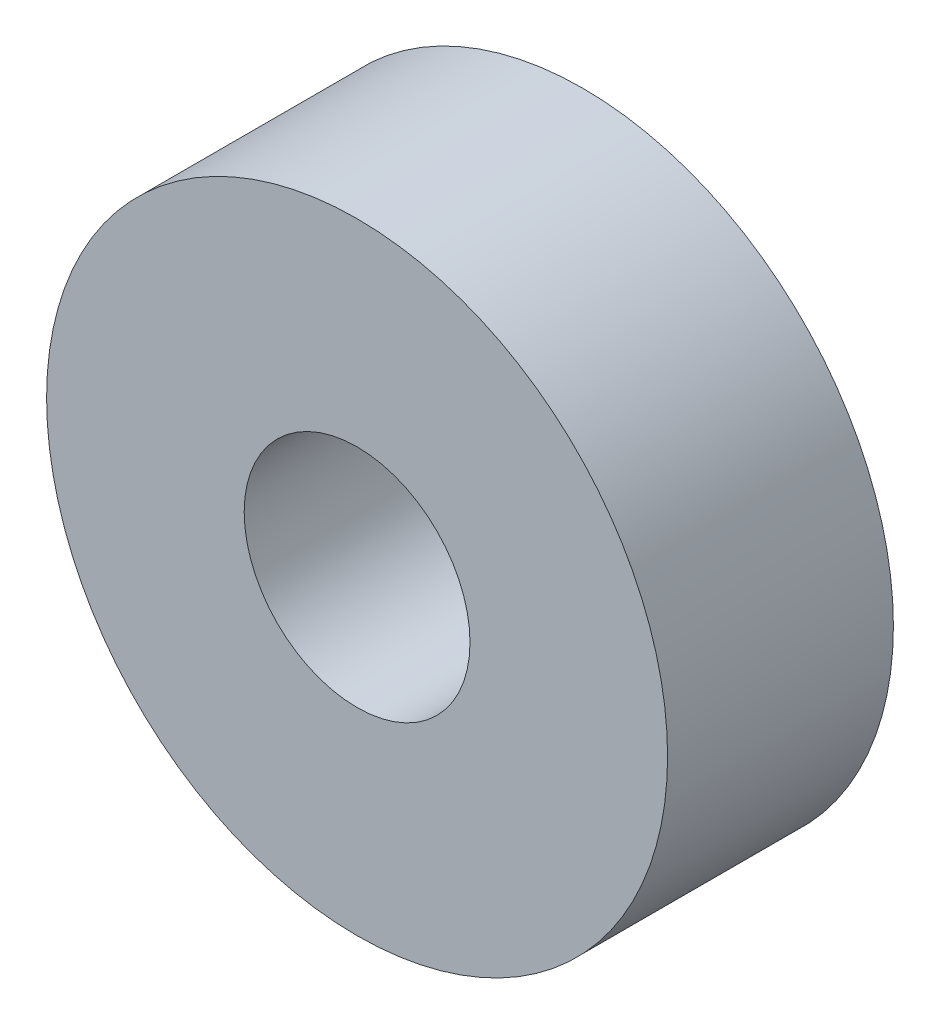
SolidWorks part; units mm, degrees
ref_plane "Спереди" through (0, 0, 0) normal (0, 0, 1) x (1, 0, 0)
ref_plane "Сверху" through (0, 0, 0) normal (0, 1, 0) x (1, 0, 0)
ref_plane "Справа" through (0, 0, 0) normal (1, 0, 0) x (0, 0, -1)
sketch "Эскиз1" plane through (0, 0, 0) normal (0, 0, 1) x (1, 0, 0)
  circle A0 centre (0, 0) radius 5.5
  circle A1 centre (0, 0) radius 2
  dimension "D1" = 4
  dimension "D2" = 11
extrude "Бобышка-Вытянуть1" add sketch "Эскиз1" along normal blind 4
